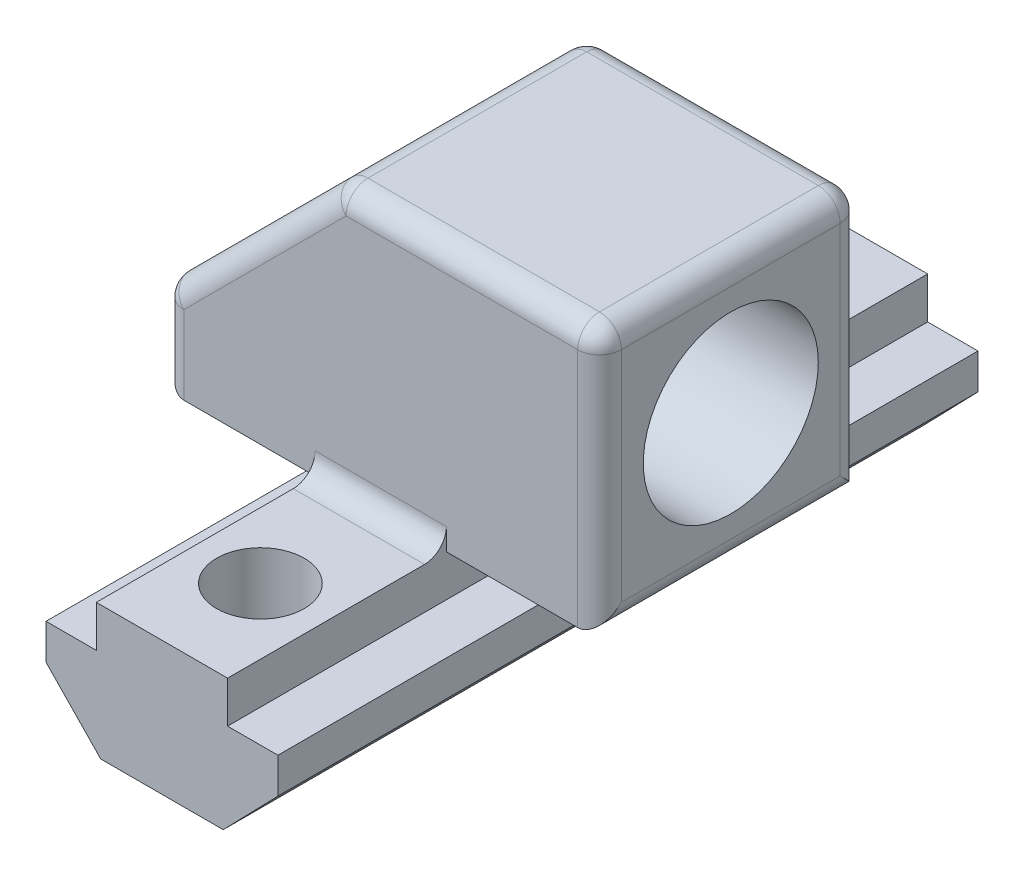
SolidWorks part; units mm, degrees
ref_plane "Front (XY)" through (0, 0, 0) normal (0, 0, 1) x (1, 0, 0)
ref_plane "Top (XZ)" through (0, 0, 0) normal (0, 1, 0) x (1, 0, 0)
ref_plane "Right (YZ)" through (0, 0, 0) normal (1, 0, 0) x (0, 0, -1)
sketch "Sketch1" plane through (0, 0, 0) normal (0, 0, 1) x (1, 0, 0)
  line L0 (0, 0) -> (0, 6.1) construction
  line L1 (-3, 6.1) -> (3, 6.1)
  line L2 (-3, 6.1) -> (-3, 4.2)
  line L3 (3, 6.1) -> (3, 4.2)
  line L4 (-3, 4.2) -> (-5.3, 4.2)
  line L5 (3, 4.2) -> (5.3, 4.2)
  line L6 (-5.3, 4.2) -> (-5.3, 2.58)
  line L7 (5.3, 4.2) -> (5.3, 2.58)
  line L8 (-2.8, 0) -> (2.8, 0)
  line L9 (-2.8, 0) -> (-5.3, 2.58)
  line L10 (2.8, 0) -> (5.3, 2.58)
  point P4 (0, 6.1)
  point P13 (0, 0)
  dimension "D1" = 6.1
  dimension "D2" = 2.3
  dimension "D3" = 1.62
  dimension "D4" = 6
  dimension "D5" = 1.9
  dimension "D6" = 5.6
extrude "Boss-Extrude1" add sketch "Sketch1" along normal mid plane 32
ref_plane "Plane1" through (0, 6.1, 0) normal (0, 1, 0) x (1, 0, 0)
sketch "Sketch2" plane through (0, 6.1, 0) normal (0, 1, 0) x (1, 0, 0)
  line L0 (-10, 5.9989) -> (10, 5.9989)
  line L1 (-10, -5.9989) -> (10, -5.9989)
  line L2 (-10, 5.9989) -> (-10, -5.9989)
  line L3 (10, 5.9989) -> (10, -5.9989)
  point P4 (0, 5.9989)
  point P5 (10, 0)
  dimension "D1" = 20
  dimension "D2" = 11.9979
extrude "Boss-Extrude2" add sketch "Sketch2" along normal blind 12
chamfer "Chamfer1" distance 8 angle 45 1 edges at (-10, 18.1, 0)
fillet "Fillet1" radius 1 15 edges at (0, 6.1, -5.9989) (0, 6.1, 5.9989) (-10, 6.1, 0) (-10, 8.1, 5.9989) (-10, 8.1, -5.9989) (10, 6.1, 0) (-6, 14.1, 5.9989) (-6, 14.1, -5.9989) (4, 18.1, -5.9989) (4, 18.1, 5.9989) (10, 12.1, -5.9989) (10, 18.1, 0) (10, 12.1, 5.9989) (-2, 18.1, 0) (-10, 10.1, 0)
sketch "Sketch3" plane through (0, 0, 0) normal (1, 0, 0) x (0, 0, -1)
  line L0 (0, 0) -> (0, 12.1) construction
  line L1 (-16, 0) -> (16, 0) construction
  circle A0 centre (0, 12.1) radius 4
  dimension "D1" = 8
  dimension "D2" = 12.1
extrude "Cut-Extrude1" cut sketch "Sketch3" against normal through all both and the other way through all
sketch "Sketch4" plane through (0, 6.1, 0) normal (0, 1, 0) x (1, 0, 0)
  line L0 (3, 16) -> (-3, 16) construction
  line L1 (3, -16) -> (-3, -16) construction
  circle A0 centre (0, 11.5) radius 2
  circle A1 centre (0, -11.5) radius 2
  dimension "D1" = 4
  dimension "D2" = 4.5
  dimension "D3" = 4.5
extrude "Cut-Extrude2" cut sketch "Sketch4" against normal through all
